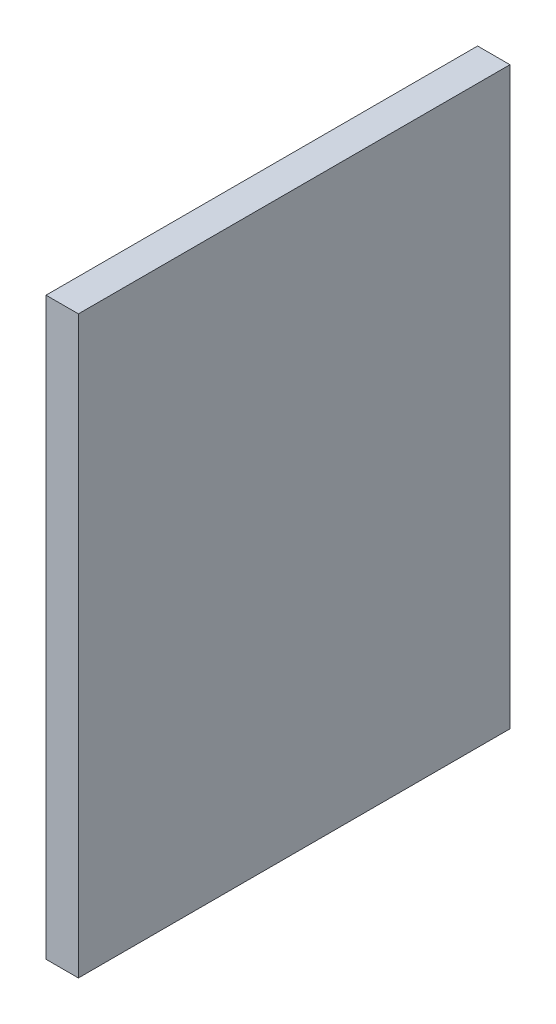
SolidWorks part; units mm, degrees
ref_plane "Front Plane" through (0, 0, 0) normal (0, 0, 1) x (1, 0, 0)
ref_plane "Top Plane" through (0, 0, 0) normal (0, 1, 0) x (1, 0, 0)
ref_plane "Right Plane" through (0, 0, 0) normal (1, 0, 0) x (0, 0, -1)
sketch "Sketch1" plane through (0, 0, 0) normal (1, 0, 0) x (0, 0, -1)
  line L1 (-20, 18.2734) -> (20, 18.2734)
  line L2 (-20, 18.2734) -> (-20, -35.0373)
  line L3 (-20, -35.0373) -> (20, -35.0373)
  line L4 (20, 18.2734) -> (20, -35.0373)
  line L5 (-20, 18.2734) -> (20, -35.0373) construction
  line L6 (-20, -35.0373) -> (20, 18.2734) construction
  point P0 (0, -8.3819)
  dimension "D1" = 40
extrude "Boss-Extrude1" add sketch "Sketch1" along normal blind 3
